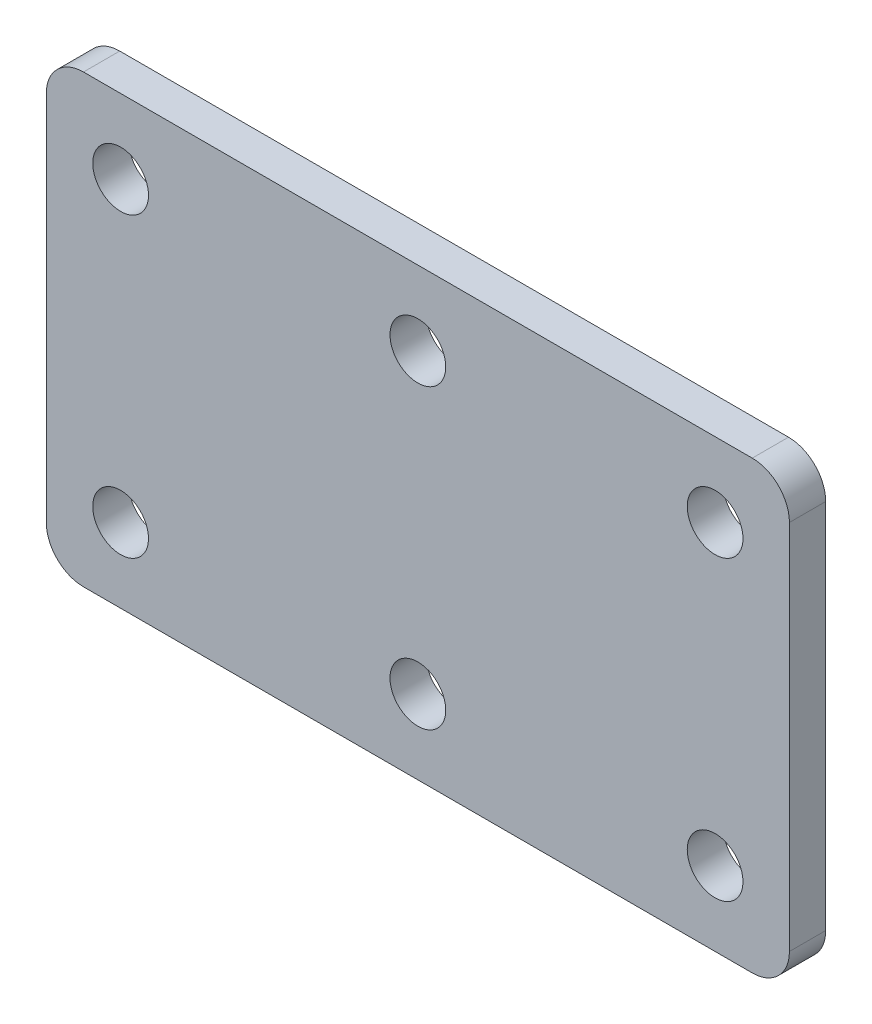
SolidWorks part; units mm, degrees
ref_plane "Front Plane" through (0, 0, 0) normal (0, 0, 1) x (1, 0, 0)
ref_plane "Top Plane" through (0, 0, 0) normal (0, 1, 0) x (1, 0, 0)
ref_plane "Right Plane" through (0, 0, 0) normal (1, 0, 0) x (0, 0, -1)
sketch "Sketch1" plane through (0, 0, 0) normal (0, 0, 1) x (1, 0, 0)
  line L0 (-38.1, 0) -> (38.1, 0) construction
  line L1 (38.1, -25.4) -> (-38.1, -25.4)
  line L2 (38.1, -25.4) -> (38.1, 25.4)
  line L3 (38.1, 25.4) -> (-38.1, 25.4)
  line L4 (-38.1, -25.4) -> (-38.1, 25.4)
  line L5 (38.1, -25.4) -> (-38.1, 25.4) construction
  line L6 (38.1, 25.4) -> (-38.1, -25.4) construction
  line L7 (0, -25.4) -> (0, 25.4) construction
  line L8 (38.1, 12.7) -> (-38.1, 12.7) construction
  circle A0 centre (-25.4, 12.7) radius 2.3813
  circle A2 centre (0, 12.7) radius 2.3813
  circle A4 centre (25.4, 12.7) radius 2.3813
  circle A5 centre (25.4, -12.7) radius 2.3813
  circle A7 centre (0, -12.7) radius 2.3813
  circle A9 centre (-25.4, -12.7) radius 2.3813
  arc A10 (-15.0812, 12.7) -> (-10.3187, 12.7) centre (-12.7, 12.7) ccw [skipped]
  arc A11 (10.3188, 12.7) -> (15.0813, 12.7) centre (12.7, 12.7) ccw [skipped]
  point P0 (0, 0)
  dimension "D4" = 4.7625
  dimension "D1" = 76.2
  dimension "D2" = 50.8
  dimension "D3" = 12.7
  dimension "D5" = 25.4
  dimension "D6" = 5
extrude "Boss-Extrude1" add sketch "Sketch1" along normal blind 3.0988
fillet "Fillet1" radius 3.175 4 edges at (38.1, 25.4, 1.5494) (38.1, -25.4, 1.5494) (-38.1, -25.4, 1.5494) (-38.1, 25.4, 1.5494)
sketch "Sketch2" plane through (0, 0, 3.0988) normal (0, 0, 1) x (1, 0, 0)
  line L0 (31.75, 19.05) -> (-31.75, 19.05)
  line L1 (-31.75, 19.05) -> (-31.75, -19.05)
  line L2 (-31.75, -19.05) -> (31.75, -19.05)
  line L3 (31.75, -19.05) -> (31.75, 19.05)
  line L4 (38.1, -22.225) -> (38.1, 22.225)
  line L5 (34.925, 25.4) -> (-34.925, 25.4)
  line L6 (-38.1, 22.225) -> (-38.1, -22.225)
  line L7 (-34.925, -25.4) -> (34.925, -25.4)
  line L8 (38.1, -22.225) -> (38.1, 22.225)
  line L9 (34.925, 25.4) -> (-34.925, 25.4)
  line L10 (-38.1, 22.225) -> (-38.1, -22.225)
  line L11 (-34.925, -25.4) -> (34.925, -25.4)
  arc A0 (-31.75, 19.05) -> (-31.75, 19.05) centre (-31.75, 19.05) ccw
  arc A1 (-31.75, -19.05) -> (-31.75, -19.05) centre (-31.75, -19.05) ccw
  arc A2 (31.75, -19.05) -> (31.75, -19.05) centre (31.75, -19.05) ccw
  arc A3 (31.75, 19.05) -> (31.75, 19.05) centre (31.75, 19.05) ccw
  arc A4 (38.1, 22.225) -> (34.925, 25.4) centre (34.925, 22.225) ccw
  arc A5 (-34.925, 25.4) -> (-38.1, 22.225) centre (-34.925, 22.225) ccw
  arc A6 (-38.1, -22.225) -> (-34.925, -25.4) centre (-34.925, -22.225) ccw
  arc A7 (34.925, -25.4) -> (38.1, -22.225) centre (34.925, -22.225) ccw
  arc A8 (38.1, 22.225) -> (34.925, 25.4) centre (34.925, 22.225) ccw
  arc A9 (-34.925, 25.4) -> (-38.1, 22.225) centre (-34.925, 22.225) ccw
  arc A10 (-38.1, -22.225) -> (-34.925, -25.4) centre (-34.925, -22.225) ccw
  arc A11 (34.925, -25.4) -> (38.1, -22.225) centre (34.925, -22.225) ccw
  dimension "D1" = 0
  dimension "D2" = 6.35
extrude "Cut-Extrude1" cut sketch "Sketch2" against normal through all
sketch "Sketch3" plane through (0, 0, 3.0988) normal (0, 0, 1) x (1, 0, 0)
  line L0 (-25.4, 12.7) -> (-25.4, -12.7) construction
  line L1 (0, -12.7) -> (0, 12.7) construction
  line L2 (0, 12.7) -> (-25.4, 12.7) construction
  line L3 (0, -12.7) -> (-25.4, 12.7) construction
  line L4 (-25.4, -12.7) -> (0, -12.7) construction
  line L5 (-31.75, 0) -> (31.75, 0) construction
  line L6 (0.3977, -6.3625) -> (0, -5.9648)
  line L7 (-30.1625, 8.4999) -> (-30.1625, -8.4999)
  line L8 (11.4977, -17.4625) -> (-22.0324, 16.0676) construction
  line L9 (-25.4, -17.4625) -> (11.4977, -17.4625) construction
  line L10 (-21.1999, -17.4625) -> (-4.2001, -17.4625)
  line L11 (-30.1625, 12.7) -> (-30.1625, -12.7) construction
  line L12 (-20.6375, 1.2023) -> (-20.6375, -7.9375)
  line L13 (-20.6375, -7.9375) -> (-11.4977, -7.9375)
  line L14 (-11.4977, -7.9375) -> (-20.6375, 1.2023)
  line L15 (-25.4, -17.4625) -> (0, -17.4625) construction
  line L16 (-31.75, 19.05) -> (-31.75, -19.05) construction
  line L17 (31.75, -19.05) -> (31.75, 19.05) construction
  line L18 (-4.2001, 17.4625) -> (-21.1999, 17.4625)
  line L19 (-4.7625, 7.9375) -> (-13.9023, 7.9375)
  line L20 (-4.7625, -1.2023) -> (-13.9023, 7.9375)
  line L21 (0, 17.4625) -> (-25.4, 17.4625) construction
  line L22 (-4.7625, -1.2023) -> (-4.7625, 7.9375)
  line L23 (25.4, 12.7) -> (25.4, -12.7) construction
  line L24 (4.7625, -1.2023) -> (4.7625, 7.9375)
  line L25 (4.7625, -1.2023) -> (13.9023, 7.9375)
  line L26 (4.7625, 7.9375) -> (13.9023, 7.9375)
  line L27 (4.2001, 17.4625) -> (21.1999, 17.4625)
  line L28 (11.4977, -7.9375) -> (20.6375, 1.2023)
  line L29 (20.6375, -7.9375) -> (11.4977, -7.9375)
  line L30 (20.6375, 1.2023) -> (20.6375, -7.9375)
  line L31 (21.1999, -17.4625) -> (4.2001, -17.4625)
  line L32 (30.1625, 8.4999) -> (30.1625, -8.4999)
  arc A0 (-21.1999, 17.4625) -> (-30.1625, 8.4999) centre (-25.4, 12.7) ccw
  arc A1 (4.2001, 17.4625) -> (-4.2001, 17.4625) centre (0, 12.7) ccw
  arc A2 (30.1625, -8.4999) -> (21.1999, -17.4625) centre (25.4, -12.7) cw
  arc A3 (21.1999, 17.4625) -> (30.1625, 8.4999) centre (25.4, 12.7) cw
  arc A4 (-4.2001, -17.4625) -> (4.2001, -17.4625) centre (0, -12.7) ccw
  arc A5 (-30.1625, -8.4999) -> (-21.1999, -17.4625) centre (-25.4, -12.7) ccw
  point P39 (-4.7625, -12.7)
  point P42 (-4.7625, 12.7)
  line M16 (-31.75, -19.05) -> (31.75, -19.05)
  line M17 (31.75, -19.05) -> (31.75, 19.05)
  line M18 (31.75, 19.05) -> (-31.75, 19.05)
  line M19 (-31.75, 19.05) -> (-31.75, -19.05)
  dimension "D1" = 4.7625
  dimension "D2" = 4.7625
  dimension "D3" = 4.7625
  dimension "D4" = 4.7625
extrude "Cut-Extrude2" [suppressed] cut sketch "Sketch3" against normal through all contours L13 L14 L12 | L20 L22 L19 | L26 L24 L25 | L30 L28 L29 | A4 A2 L31 M16 | A5 A4 L10 M16 | A5 M19 M16 | A5 L7 A0 M19 | A0 M18 M19 | A1 A0 L18 M18 | L27 A3 A1 M18 | A3 M18 M17 | A3 L32 A2 M17 | A2 M17 M16
fillet "Fillet2" [suppressed] radius 1.5875
fillet "Fillet3" radius 3.175 4 edges at (31.75, -19.05, 1.5494) (31.75, 19.05, 1.5494) (-31.75, -19.05, 1.5494) (-31.75, 19.05, 1.5494)
